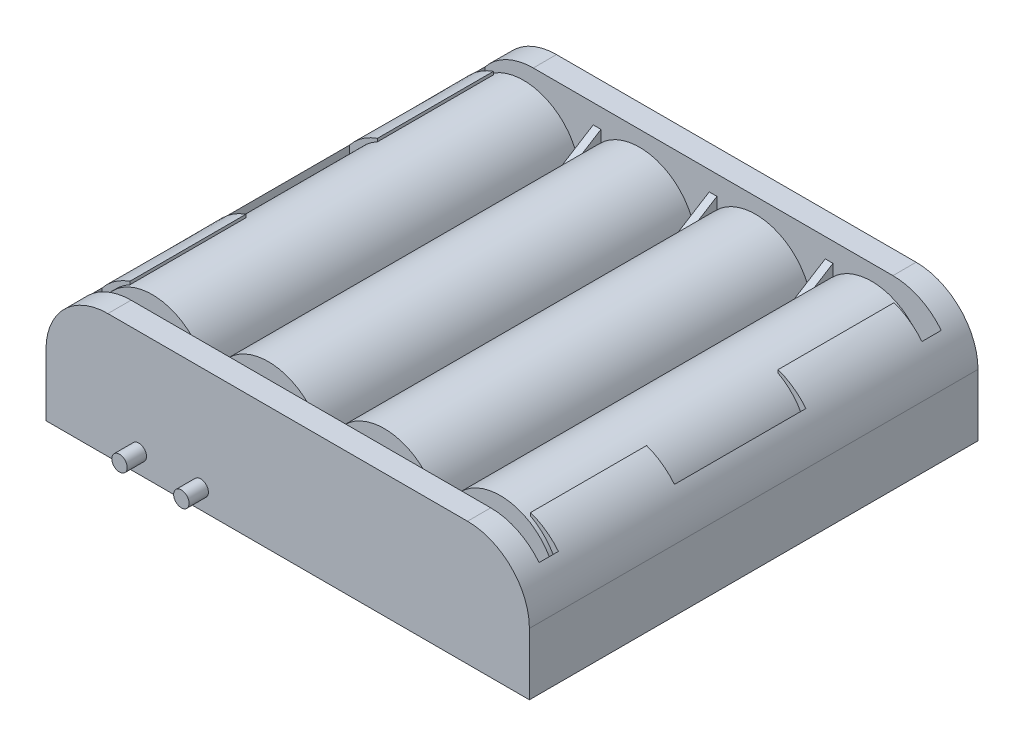
SolidWorks part; units mm, degrees
ref_plane "Front Plane" through (0, 0, 0) normal (0, 0, 1) x (1, 0, 0)
ref_plane "Top Plane" through (0, 0, 0) normal (0, 1, 0) x (1, 0, 0)
ref_plane "Right Plane" through (0, 0, 0) normal (1, 0, 0) x (0, 0, -1)
sketch "Sketch1" plane through (0, 0, 0) normal (0, 1, 0) x (1, 0, 0)
  line L1 (-31.25, -29) -> (31.25, -29)
  line L2 (-31.25, -29) -> (-31.25, 29)
  line L3 (-31.25, 29) -> (31.25, 29)
  line L4 (31.25, -29) -> (31.25, 29)
  line L5 (-31.25, -29) -> (31.25, 29) construction
  line L6 (-31.25, 29) -> (31.25, -29) construction
  point P0 (0, 0)
  dimension "D1" = 62.5
  dimension "D2" = 58
extrude "Boss-Extrude1" add sketch "Sketch1" along normal blind 16
fillet "Fillet1" radius 8 2 edges at (31.25, 16, 0) (-31.25, 16, 0)
sketch "Sketch2" plane through (0, 16, 0) normal (0, 1, 0) x (1, 0, 0)
  line L0 (0, 0) -> (0, 26) construction
  line L1 (-29.5, 26) -> (-15.5, 26)
  line L2 (-29.5, 26) -> (-29.5, 23.5)
  line L3 (-29.5, -26) -> (-15.5, -26)
  line L4 (-15.5, 26) -> (-15.5, -26)
  line L5 (-14.5, 26) -> (-0.5, 26)
  line L6 (-14.5, 26) -> (-14.5, -26)
  line L7 (-14.5, -26) -> (-0.5, -26)
  line L8 (-0.5, 26) -> (-0.5, -26)
  line L9 (15.5, 26) -> (29.5, 26)
  line L10 (15.5, 26) -> (15.5, -26)
  line L11 (15.5, -26) -> (29.5, -26)
  line L12 (29.5, 26) -> (29.5, 23.5)
  line L13 (0, 0) -> (-0.5, 0) construction
  line L14 (29.5, 8.5) -> (25.9, 8.5)
  line L15 (29.5, -23.5) -> (25.9, -23.5)
  line L17 (29.5, -8.5) -> (25.9, -8.5)
  line L18 (25.9, -23.5) -> (25.9, -8.5)
  line L19 (25.9, 23.5) -> (25.9, 8.5)
  line L20 (29.5, 23.5) -> (25.9, 23.5)
  line L23 (-29.5, 23.5) -> (-25.9, 23.5)
  line L24 (-25.9, 23.5) -> (-25.9, 8.5)
  line L25 (-29.5, 8.5) -> (-25.9, 8.5)
  line L26 (-29.5, -8.5) -> (-25.9, -8.5)
  line L27 (-25.9, -23.5) -> (-25.9, -8.5)
  line L28 (-29.5, -23.5) -> (-25.9, -23.5)
  line L30 (-29.5, 8.5) -> (-29.5, -8.5)
  line L31 (-29.5, -23.5) -> (-29.5, -26)
  line L32 (29.5, 8.5) -> (29.5, -8.5)
  line L33 (29.5, -23.5) -> (29.5, -26)
  line L34 (-15.5, -26) -> (-14.5, -26) construction
  line L35 (0.5, 26) -> (14.5, 26)
  line L36 (0.5, 26) -> (0.5, -26)
  line L37 (0.5, -26) -> (14.5, -26)
  line L38 (14.5, 26) -> (14.5, -26)
  line L39 (-0.5, -26) -> (0.5, -26) construction
  point P36 (14.2249, 26)
  dimension "D1" = 14
  dimension "D2" = 52
  dimension "D3" = 1
  dimension "D4" = 3.6
  dimension "D5" = 15
  dimension "D6" = 17
extrude "Cut-Extrude1" cut sketch "Sketch2" against normal blind 14
sketch "Sketch3" plane through (15.5, 0, 0) normal (1, 0, 0) x (0, 0, -1)
  line L0 (-26, 16) -> (-26, 13.5)
  line L1 (-26, 12.9937) -> (-26, 16) construction
  line L2 (-26, 13.5) -> (-17.5, 8.2)
  line L3 (-17.5, 8.2) -> (17.5, 8.2)
  line L4 (0, 0) -> (0, 8.2) construction
  line L5 (-29, 0) -> (29, 0) construction
  line L6 (26, 16) -> (-26, 16) construction
  line L7 (26, 16) -> (26, 13.5)
  line L8 (26, 13.5) -> (17.5, 8.2)
  line L9 (26, 16) -> (-26, 16)
  dimension "D1" = 2.5
  dimension "D2" = 7.8
  dimension "D3" = 8.5
extrude "Cut-Extrude2" cut sketch "Sketch3" against normal up to surface (31 mm away) up to face at (-15.5, 9, 0)
sketch "Sketch4" plane through (0, 0, 0) normal (0, 0, 1) x (1, 0, 0)
  line L0 (-15.5, 2) -> (-29.5, 2) construction
  line L1 (-15.5, 2) -> (-29.5, 2) construction
  line L2 (-0.5, 2) -> (-14.5, 2) construction
  line L3 (-0.5, 2) -> (-14.5, 2) construction
  line L4 (29.5, 2) -> (15.5, 2) construction
  line L5 (29.5, 2) -> (15.5, 2) construction
  line L6 (-23.25, 16) -> (23.25, 16) construction
  line L7 (-22.5, 8.75) -> (-7.5, 8.75) construction
  line L8 (-7.5, 8.75) -> (7.5, 8.75) construction
  line L9 (7.5, 8.75) -> (22.5, 8.75) construction
  circle A0 centre (-22.5, 8.75) radius 7.25
  circle A1 centre (-7.5, 8.75) radius 7.25
  circle A2 centre (22.5, 8.75) radius 7.25
  circle A3 centre (7.5, 8.75) radius 7.25
  point P9 (-22.5, 2)
  point P14 (22.5, 2)
  dimension "D1" = 14.5
extrude "Boss-Extrude3" add sketch "Sketch4" along normal mid plane 48
sketch "Sketch6" plane through (0, 0, 29) normal (0, 0, 1) x (1, 0, 0)
  line L0 (-31.25, 8) -> (-31.25, 0) construction
  line L1 (-31.25, 0) -> (31.25, 0) construction
  circle A0 centre (-19.25, 2.5) radius 1
  circle A1 centre (-11.25, 2.5) radius 1
  dimension "D1" = 2
  dimension "D2" = 12
  dimension "D3" = 8
  dimension "D4" = 2.5
extrude "Boss-Extrude5" add sketch "Sketch6" along normal blind 2.5
